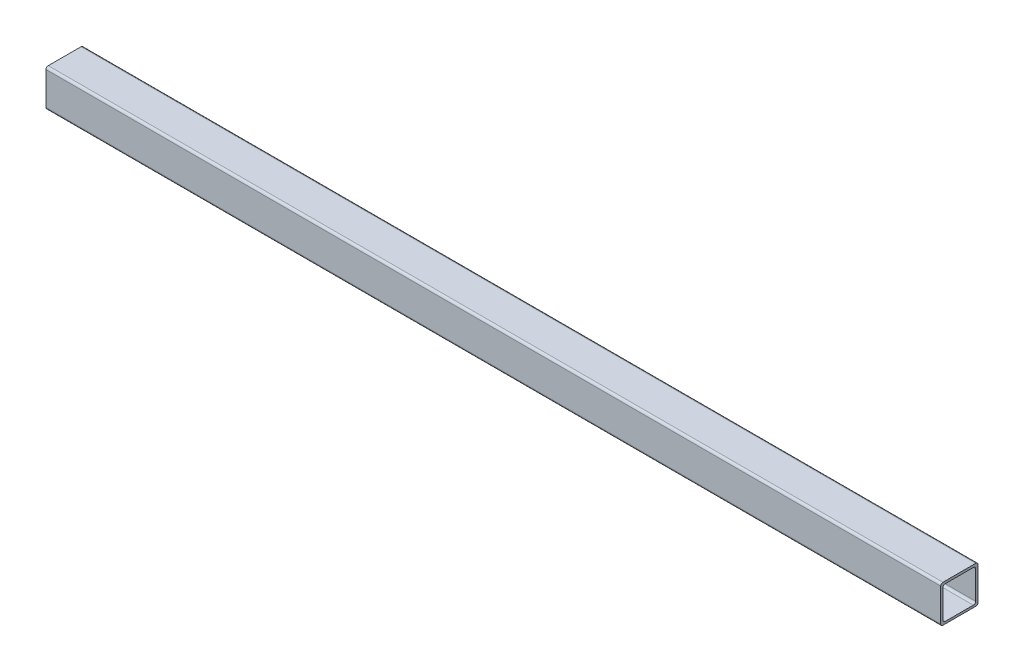
SolidWorks part; units mm, degrees
ref_plane "Front Plane" through (0, 0, 0) normal (0, 0, 1) x (1, 0, 0)
ref_plane "Top Plane" through (0, 0, 0) normal (0, 1, 0) x (1, 0, 0)
ref_plane "Right Plane" through (0, 0, 0) normal (1, 0, 0) x (0, 0, -1)
sketch "Sketch2" plane through (0, 0, 0) normal (1, 0, 0) x (0, 0, -1)
  line L1 (0.762, 0) -> (11.938, 0)
  line L2 (0, 0.762) -> (0, 11.938)
  line L3 (0.762, 12.7) -> (11.938, 12.7)
  line L4 (12.7, 0.762) -> (12.7, 11.938)
  line L5 (1.524, 0.762) -> (11.1125, 0.762)
  line L6 (0.762, 1.524) -> (0.762, 11.1125)
  line L7 (1.524, 11.8745) -> (11.1125, 11.8745)
  line L8 (11.8745, 1.524) -> (11.8745, 11.1125)
  arc A0 (11.1125, 11.8745) -> (11.8745, 11.1125) centre (11.1125, 11.1125) cw
  arc A1 (11.1125, 0.762) -> (11.8745, 1.524) centre (11.1125, 1.524) ccw
  arc A2 (1.524, 0.762) -> (0.762, 1.524) centre (1.524, 1.524) cw
  arc A3 (0.762, 11.1125) -> (1.524, 11.8745) centre (1.524, 11.1125) cw
  arc A4 (11.938, 12.7) -> (12.7, 11.938) centre (11.938, 11.938) cw
  arc A5 (11.938, 0) -> (12.7, 0.762) centre (11.938, 0.762) ccw
  arc A6 (0.762, 0) -> (0, 0.762) centre (0.762, 0.762) cw
  arc A7 (0, 11.938) -> (0.762, 12.7) centre (0.762, 11.938) cw
  point P11 (11.8745, 11.8745)
  point P14 (11.8745, 0.762)
  point P19 (0.762, 11.8745)
  point P22 (12.7, 12.7)
  point P25 (12.7, 0)
  point P28 (0, 0)
  point P31 (0, 12.7)
  dimension "D7" = 0.762
  dimension "D1" = 12.7
  dimension "D2" = 12.7
  dimension "D3" = 11.1125
  dimension "D4" = 11.1125
  dimension "D5" = 0.762
  dimension "D6" = 0.762
extrude "Boss-Extrude1" add sketch "Sketch2" along normal blind 304.8
equation "\"shaft\"=0.5"
equation "\"D1@Sketch2\"=\"shaft\""
equation "\"D2@Sketch2\"=\"shaft\""
equation "\"IDshaft\"=0.4375"
equation "\"D3@Sketch2\"=\"IDshaft\""
equation "\"D4@Sketch2\"=\"IDshaft\""
